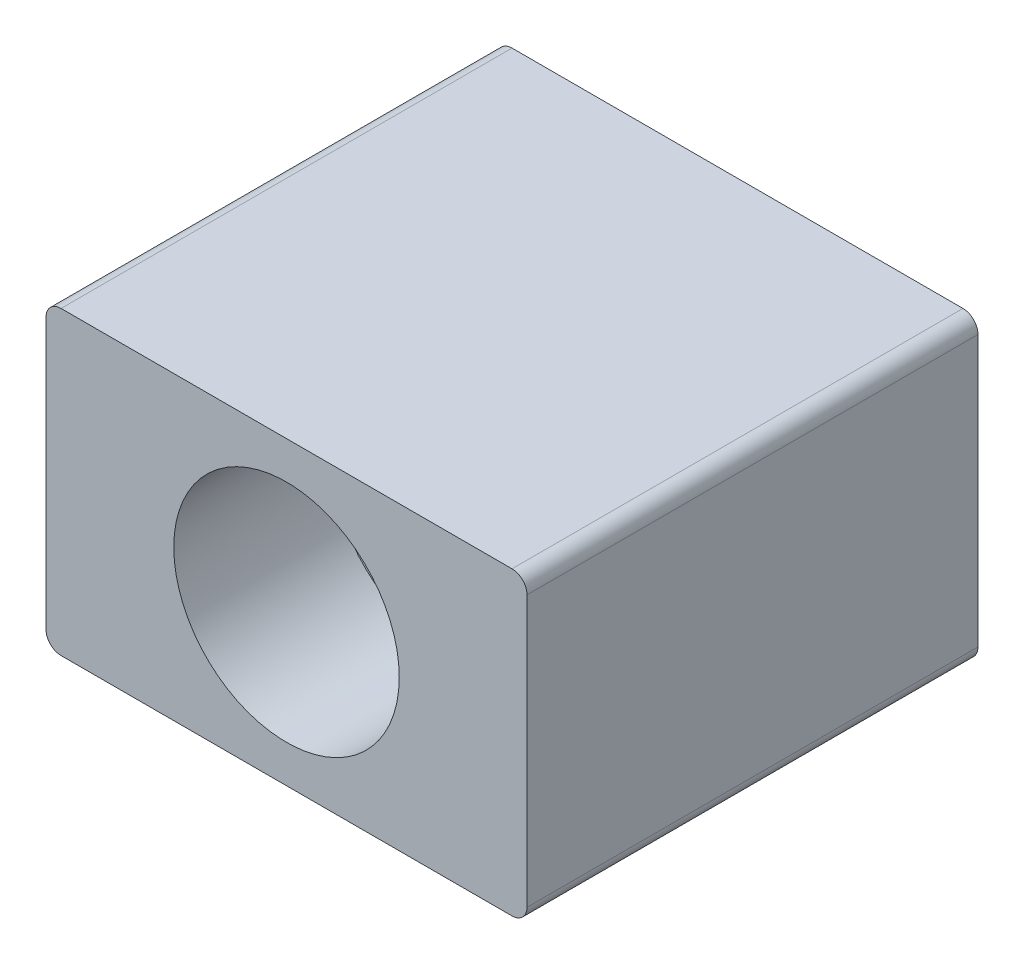
SolidWorks part; units mm, degrees
ref_plane "Front Plane" through (0, 0, 0) normal (0, 0, 1) x (1, 0, 0)
ref_plane "Top Plane" through (0, 0, 0) normal (0, 1, 0) x (1, 0, 0)
ref_plane "Right Plane" through (0, 0, 0) normal (1, 0, 0) x (0, 0, -1)
sketch "Sketch1" plane through (0, 0, 0) normal (0, 0, 1) x (1, 0, 0)
  line L1 (-15, 10) -> (15, 10)
  line L2 (-16, 9) -> (-16, -9)
  line L3 (-15, -10) -> (15, -10)
  line L4 (16, 9) -> (16, -9)
  line L5 (-16, 10) -> (16, -10) construction
  line L6 (-16, -10) -> (16, 10) construction
  arc A0 (16, 9) -> (15, 10) centre (15, 9) ccw
  arc A1 (15, -10) -> (16, -9) centre (15, -9) ccw
  arc A2 (-15, -10) -> (-16, -9) centre (-15, -9) cw
  arc A3 (-16, 9) -> (-15, 10) centre (-15, 9) cw
  circle A4 centre (0, 0) radius 5.25
  point P0 (0, 0)
  dimension "D3" = 1
  dimension "D4" = 10.5
  dimension "D1" = 32
  dimension "D2" = 20
extrude "Boss-Extrude1" add sketch "Sketch1" against normal mid plane 30
sketch "Sketch2" plane through (0, 0, 15) normal (0, 0, 1) x (1, 0, 0)
  circle A0 centre (0, 0) radius 7.5
  dimension "D1" = 15
extrude "Cut-Extrude1" cut sketch "Sketch2" against normal blind 10.5 contours A0
mirror "Mirror1" about plane through (0, 0, 0) normal (0, 0, 1) of "Cut-Extrude1"
